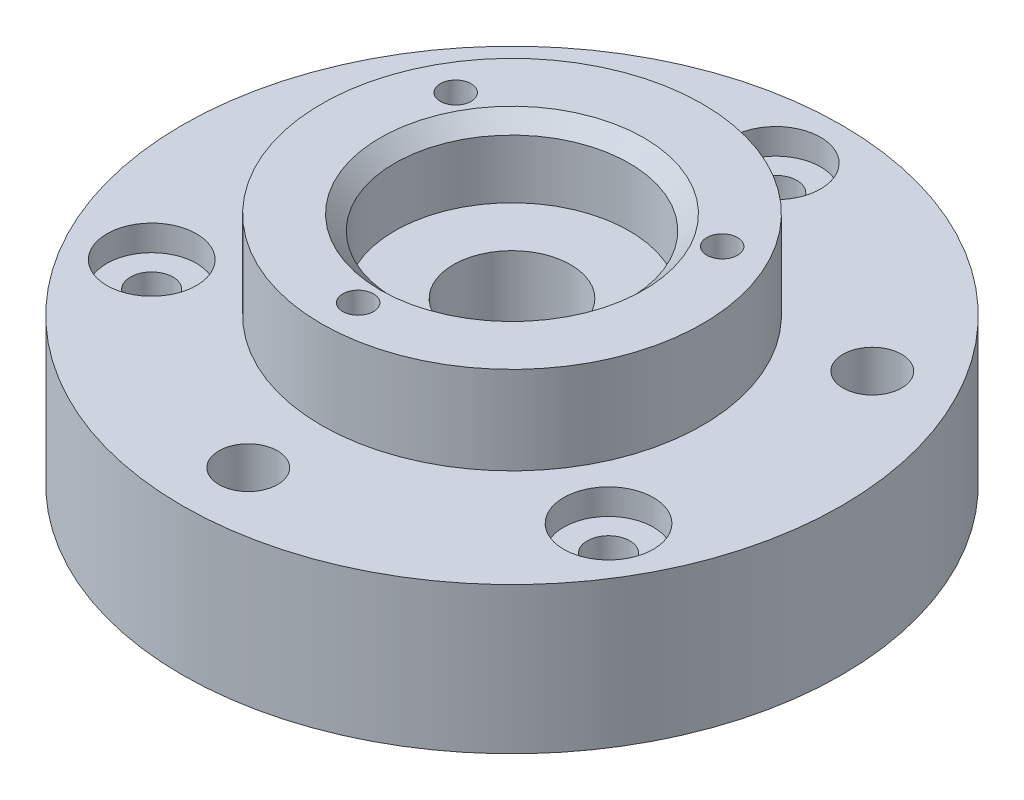
SolidWorks part; units mm, degrees
ref_plane "Front Plane" through (0, 0, 0) normal (0, 0, 1) x (1, 0, 0)
ref_plane "Top Plane" through (0, 0, 0) normal (0, 1, 0) x (1, 0, 0)
ref_plane "Right Plane" through (0, 0, 0) normal (1, 0, 0) x (0, 0, -1)
sketch "Sketch5" plane through (0, 0, 0) normal (0, 0, 1) x (1, 0, 0)
  line L0 (0, 0) -> (27.5, 0)
  line L1 (27.5, 0) -> (27.5, 5)
  line L2 (27.5, 5) -> (45, 5)
  line L3 (45, 5) -> (45, 25)
  line L4 (45, 25) -> (26, 25)
  line L5 (26, 25) -> (26, 37)
  line L6 (26, 37) -> (0, 37)
  line L7 (0, 37) -> (0, 0)
  line L8 (0, 0) -> (0, 50000) construction
  dimension "D1" = 20
  dimension "D2" = 5
  dimension "D3" = 37
  dimension "D4" = 52
  dimension "D5" = 55
  dimension "D6" = 90
revolve "Revolve4" add sketch "Sketch5" angle 360 about L8
hole_wizard "Hole1" positions "Sketch7" profile "Sketch8" legacy
sketch "Sketch7" plane through (0, 0, 0) normal (0, -1, 0) x (-1, 0, 0)
  point P0 (0, 0)
sketch "Sketch8" plane through (0, 0, 0) normal (1, 0, 0) x (0, 0, -1)
  line L0 (0, 0) -> (0, 5)
  line L1 (0, 5) -> (17.5, 5)
  line L2 (17.5, 5) -> (17.5, 0)
  line L3 (17.5, 0) -> (0, 0)
  line L4 (0, 110) -> (0, -10) construction
  dimension "Diameter" = 35
  dimension "Depth" = 5
fillet "Fillet1" radius 2 1 edges at (0, 5, -17.5)
hole_wizard "CBORE for M5 Hex Head Bolt1" positions "Sketch10" profile "Sketch11" counterbore size "M5" standard "ISO" end condition through all
sketch "Sketch10" plane through (0, 25, 0) normal (0, 1, 0) x (1, 0, 0)
  circle A0 centre (0, 0) radius 36 construction
  point P0 (0, 36)
  point P7 (0, 0)
  point P8 (0, 36)
  point P9 (0, 0)
  dimension "D1" = 72
sketch "Sketch11" plane through (0, 25, -36) normal (1, 0, 0) x (0, 0, 1)
  line L0 (0, 0) -> (0, 25)
  line L1 (0, 25) -> (2.9, 25)
  line L3 (2.9, 25) -> (2.9, 3.5)
  line L4 (2.9, 3.5) -> (6.119, 3.5)
  line L5 (6.119, 3.5) -> (6.119, 0)
  line L7 (6.119, 0) -> (0, 0)
  line L11 (0, -6.35) -> (0, 107.95) construction
  dimension "Thru Hole Dia." = 5.8
  dimension "Thru Hole Depth" = 25
  dimension "C'Bore Dia." = 12.238
  dimension "C'Bore Depth" = 3.5
hole_wizard "Ø8.0mm Dowel Hole1" positions "Sketch15" profile "Sketch16" hole size "Ø8.0" standard "ISO" end condition through all
sketch "Sketch15" plane through (0, 25, 0) normal (0, 1, 0) x (1, 0, 0)
  circle A0 centre (0, 0) radius 36 construction
  point P0 (0, -36)
  dimension "D1" = 72
sketch "Sketch16" plane through (0, 25, 36) normal (1, 0, 0) x (0, 0, 1)
  line L0 (0, 0) -> (0, 25)
  line L1 (0, 25) -> (4, 25)
  line L2 (4, 25) -> (4, 0)
  line L5 (4, 0) -> (0, 0)
  line L11 (0, -6.35) -> (0, 107.95) construction
  dimension "Thru Hole Dia." = 8
  dimension "Thru Hole Depth" = 25
hole_wizard "Hole2" positions "Sketch19" profile "Sketch20" legacy end condition through all
sketch "Sketch19" plane through (0, 37, 0) normal (0, 1, 0) x (1, 0, 0)
  point P0 (0, 0)
sketch "Sketch20" plane through (0, 37, 0) normal (1, 0, 0) x (0, 0, 1)
  line L0 (0, 0) -> (0, 37)
  line L1 (0, 37) -> (8, 37)
  line L2 (8, 37) -> (8, 10)
  line L3 (8, 10) -> (16, 10)
  line L4 (16, 10) -> (16, 0)
  line L5 (16, 0) -> (0, 0)
  line L6 (0, 110) -> (0, -10) construction
  dimension "Diameter" = 16
  dimension "Depth" = 37
  dimension "C-Bore Diameter" = 32
  dimension "C-Bore Depth" = 10
chamfer "Chamfer1" distance 2 angle 45 1 edges at (0, 37, 16)
hole_wizard "M5 Tapped Hole1" positions "Sketch21" profile "Sketch22" tap size "M5" standard "ISO"
sketch "Sketch21" plane through (0, 37, 0) normal (0, 1, 0) x (1, 0, 0)
  line L0 (0, 0) -> (0, -50000) construction
  circle A0 centre (0, 0) radius 21 construction
  point P0 (0, -21)
  point P12 (0, 0)
  dimension "D1" = 42
cosmetic thread "Hole Thread1"
sketch "Sketch22" plane through (0, 37, 21) normal (1, 0, 0) x (0, 0, 1)
  line L0 (0, 0) -> (0, 14.2618)
  line L1 (0, 14.2618) -> (2.1, 13)
  line L2 (2.1, 13) -> (2.1, 0)
  line L5 (2.1, 0) -> (0, 0)
  line L10 (0, 14.2618) -> (-2.1, 13) construction
  line L11 (0, -6.35) -> (0, 107.95) construction
  dimension "Tap Drill Dia." = 4.2
  dimension "Tap Drill Depth" = 13
  dimension "Drill Angle" = 118
pattern_circular "CirPattern4" count 3 over 360 about axis through (0, 0, 0) along (0, 1, 0) of "CBORE for M5 Hex Head Bolt1", "Ø8.0mm Dowel Hole1", "M5 Tapped Hole1"
cosmetic thread "Hole Thread4"
cosmetic thread "Hole Thread5"
ref_plane "Plane1" through (-45, 0, 0) normal (-1, 0, 0) x (0, 0, 1)
hole_wizard "Ø10.0 (10) Diameter Hole1" positions "Sketch25" profile "Sketch26" hole size "Ø10.0" standard "ISO"
sketch "Sketch25" plane through (-45, 0, 0) normal (-1, 0, 0) x (0, 0, 1)
  line L0 (-27.5, 5) -> (27.5, 5) construction
  point P0 (0, 15)
  point P6 (0, 0)
  dimension "D1" = 10
sketch "Sketch26" plane through (-45, 15, 0) normal (0, 1, 0) x (0, 0, 1)
  line L0 (0, 0) -> (0, 35.0043)
  line L1 (0, 35.0043) -> (5, 32)
  line L2 (5, 32) -> (5, 0)
  line L5 (5, 0) -> (0, 0)
  line L10 (0, 35.0043) -> (-5, 32) construction
  line L11 (0, -6.35) -> (0, 107.95) construction
  dimension "Hole Dia." = 10
  dimension "Hole Depth" = 32
  dimension "Drill Angle" = 118
hole_wizard "Ø10.0 (10) Diameter Hole2" positions "Sketch27" profile "Sketch28" hole size "Ø10.0" standard "ISO"
sketch "Sketch27" plane through (0, 0, 0) normal (0, -1, 0) x (1, 0, 0)
  point P0 (-18, 0)
  dimension "D1" = 18
sketch "Sketch28" plane through (-18, 0, 0) normal (1, 0, 0) x (0, 0, -1)
  line L0 (0, 0) -> (0, 10)
  line L1 (0, 10) -> (5, 10)
  line L2 (5, 10) -> (5, 0)
  line L5 (5, 0) -> (0, 0)
  line L11 (0, -6.35) -> (0, 107.95) construction
  dimension "Thru Hole Dia." = 10
  dimension "Thru Hole Depth" = 10
